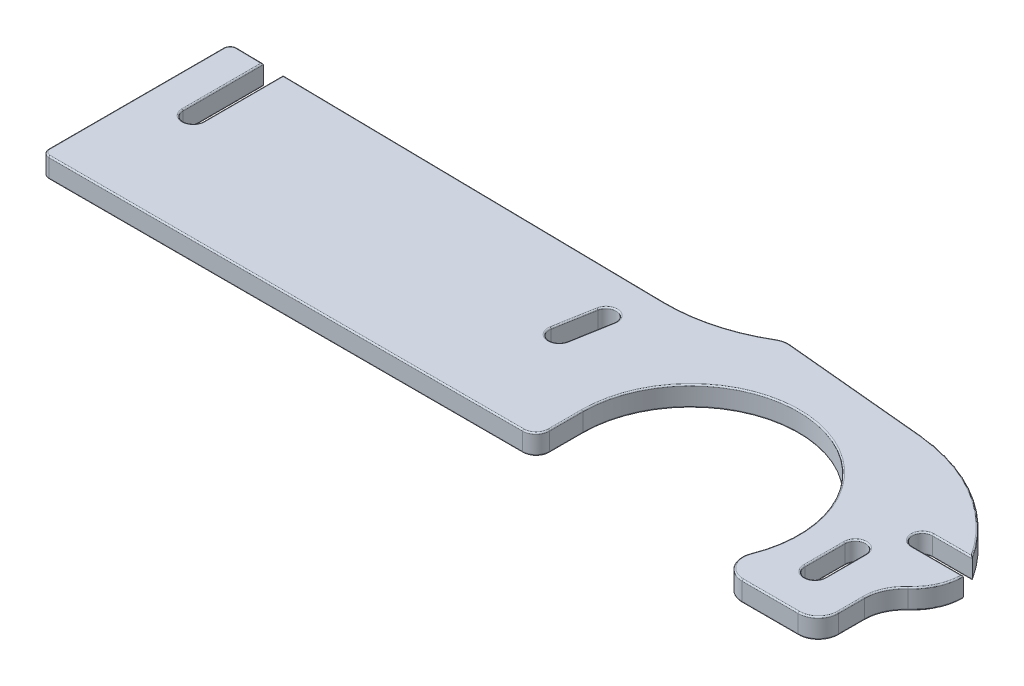
SolidWorks part; units mm, degrees
ref_plane "Front Plane" through (0, 0, 0) normal (0, 0, 1) x (1, 0, 0)
ref_plane "Top Plane" through (0, 0, 0) normal (0, 1, 0) x (1, 0, 0)
ref_plane "Right Plane" through (0, 0, 0) normal (1, 0, 0) x (0, 0, -1)
sketch "Sketch1" plane through (0, 0, 0) normal (0, 1, 0) x (1, 0, 0)
  line L0 (-24, 20) -> (-81.5, 20.8779)
  line L1 (-81.5, 20.8779) -> (-81.5, 9)
  line L2 (-84.5, 20.9237) -> (-84.5, 9)
  line L3 (-84.5, 20.9237) -> (-88.4847, 20.9845)
  line L4 (22, 2.5) -> (22, -3.5) construction
  line L5 (23.5, 2.5) -> (23.5, -3.5)
  line L6 (20.5, 2.5) -> (20.5, -3.5)
  line L7 (17.6635, -10) -> (26, -10)
  line L8 (12.4341, 21.8858) -> (-9.0463, 23.9057)
  line L9 (29, -7) -> (29, -3.1406)
  line L10 (-18, -7) -> (-88.5, -7)
  line L11 (-26.5, 13.9088) -> (-27.5419, 8) construction
  line L12 (-89.5, 19.9846) -> (-89.5, -6)
  line L13 (-16, 0) -> (-16, -5)
  line L14 (26, 10) -> (31.9089, 10)
  line L15 (26, 7) -> (33.5584, 7)
  line L16 (-25.0228, 13.6484) -> (-26.0647, 7.7395)
  line L17 (-27.9772, 14.1693) -> (-29.0191, 8.2605)
  arc A0 (14.8745, -5.8947) -> (-16, 0) centre (0, 0) ccw
  arc A1 (31.0172, 1.3469) -> (33.5584, 7) centre (26, 7) ccw
  arc A2 (-84.5, 9) -> (-81.5, 9) centre (-83, 9) ccw
  arc A3 (23.5, 2.5) -> (20.5, 2.5) centre (22, 2.5) ccw
  arc A4 (20.5, -3.5) -> (23.5, -3.5) centre (22, -3.5) ccw
  arc A5 (-24, 20) -> (-10.8583, 23.4987) centre (-23.6184, 44.9971) ccw
  arc A6 (26, 10) -> (26, 7) centre (26, 8.5) ccw
  arc A7 (31.9089, 10) -> (12.4341, 21.8858) centre (10, -4) ccw
  arc A8 (29, -7) -> (26, -10) centre (26, -7) cw
  arc A9 (17.6635, -10) -> (14.8745, -5.8947) centre (17.6635, -7) cw
  arc A10 (-18, -7) -> (-16, -5) centre (-18, -5) ccw
  arc A11 (29, -3.1406) -> (31.0172, 1.3469) centre (35, -3.1406) cw
  arc A12 (-25.0228, 13.6484) -> (-27.9772, 14.1693) centre (-26.5, 13.9088) ccw
  arc A13 (-29.0191, 8.2605) -> (-26.0647, 7.7395) centre (-27.5419, 8) ccw
  arc A14 (-88.4847, 20.9845) -> (-89.5, 19.9846) centre (-88.5, 19.9846) ccw
  arc A15 (-88.5, -7) -> (-89.5, -6) centre (-88.5, -6) cw
  arc A16 (-10.8583, 23.4987) -> (-9.0463, 23.9057) centre (-9.3271, 20.9189) cw
  point P13 (22, -0.5)
  point P41 (-27.0209, 10.9544)
  point P48 (-89.5, 21)
  point P53 (-10.0492, 24)
  dimension "D1" = 32
  dimension "D3" = 7
  dimension "D5" = 27
  dimension "D16" = 3
  dimension "D19" = 50
  dimension "D20" = 31
  dimension "D24" = 3
  dimension "D25" = 2
  dimension "D26" = 6
  dimension "D27" = 26
  dimension "D28" = 7.5584
  dimension "D30" = 1.5
  dimension "D36" = 1
  dimension "D37" = 3
  dimension "D2" = 3
  dimension "D4" = 24
  dimension "D6" = 22
  dimension "D7" = 1.5
  dimension "D8" = 6
  dimension "D9" = 6.5
  dimension "D10" = 28
  dimension "D11" = 29
  dimension "D12" = 89.5
  dimension "D13" = 5
  dimension "D15" = 10
  dimension "D17" = 10
  dimension "D18" = 4
  dimension "D21" = 3
  dimension "D22" = 4
  dimension "D23" = 6
  dimension "D29" = 16
  dimension "D31" = 80
  dimension "D32" = 15
  dimension "D33" = 6
  dimension "D34" = 3
  dimension "D35" = 63
extrude "Boss-Extrude1" add sketch "Sketch1" along normal blind 3
fillet "Fillet1" radius 0.2 66 edges at (-25.5437, 0, -10.694) (-27.8024, 0, -6.5228) (-28.4982, 0, -11.2149) (-26.2395, 0, -15.3861) (15.182, 0, 8.6859) (21.8318, 0, 10) (28.1213, 0, 9.1213) (29, 0, 5.0703) (29.5275, 0, 0.6805) (32.8939, 0, -3.901) (29.7792, 0, -7) (24.5, 0, -8.5) (28.9545, 0, -10) (23.5449, 0, -18.1932) (1.6939, 0, -22.8957) (-9.9846, 0, -23.8459) (-17.1867, 0, -20.8386) (-52.75, 0, -20.4389) (-81.5, 0, -14.9389) (-83, 0, -7.5) (-84.5, 0, -14.9618) (-86.4924, 0, -20.9541) (-89.2017, 0, -20.6971) (-89.5, 0, -6.9923) (-89.2071, 0, 6.7071) (-53.25, 0, 7) (-16.5858, 0, 6.4142) (-16, 0, 2.5) (3.0006, 0, -15.7161) (23.5, 0, 0.5) (22, 0, 5) (20.5, 0, 0.5) (22, 0, -4) (-27.8024, 3, -6.5228) (-25.5437, 3, -10.694) (-26.2395, 3, -15.3861) (-28.4982, 3, -11.2149) (22, 3, 5) (23.5, 3, 0.5) (22, 3, -4) (20.5, 3, 0.5) (-16, 3, 2.5) (-16.5858, 3, 6.4142) (-53.25, 3, 7) (-89.2071, 3, 6.7071) (-89.5, 3, -6.9923) (-89.2017, 3, -20.6971) (-86.4924, 3, -20.9541) (-84.5, 3, -14.9618) (-83, 3, -7.5) (-81.5, 3, -14.9389) (-52.75, 3, -20.4389) (-17.1867, 3, -20.8386) (-9.9846, 3, -23.8459) (1.6939, 3, -22.8957) (23.5449, 3, -18.1932) (28.9545, 3, -10) (24.5, 3, -8.5) (29.7792, 3, -7) (32.8939, 3, -3.901) (29.5275, 3, 0.6805) (29, 3, 5.0703) (28.1213, 3, 9.1213) (21.8318, 3, 10) (15.182, 3, 8.6859) (3.0006, 3, -15.7161)
